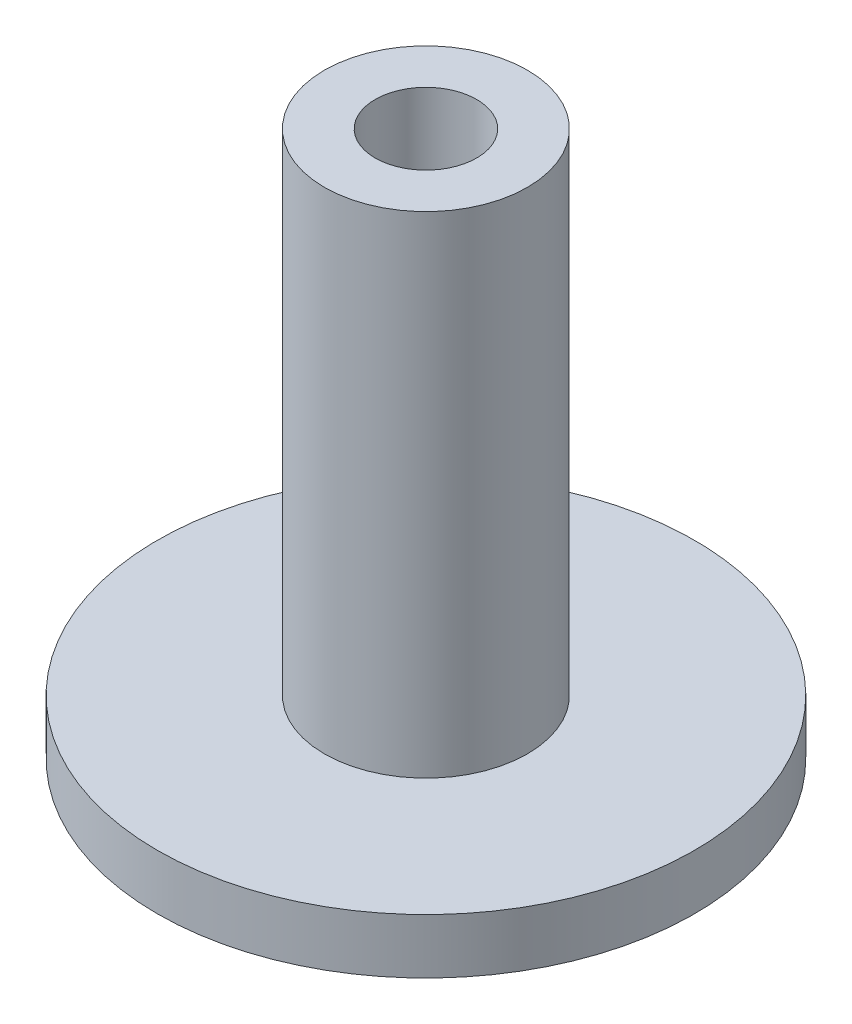
SolidWorks part; units mm, degrees
ref_plane "Front Plane" through (0, 0, 0) normal (0, 0, 1) x (1, 0, 0)
ref_plane "Top Plane" through (0, 0, 0) normal (0, 1, 0) x (1, 0, 0)
ref_plane "Right Plane" through (0, 0, 0) normal (1, 0, 0) x (0, 0, -1)
sketch "Sketch1" plane through (0, 0, 0) normal (0, 1, 0) x (1, 0, 0)
  circle A0 centre (0, 0) radius 6.35
  dimension "D1" = 12.7
extrude "Boss-Extrude1" add sketch "Sketch1" along normal blind 1.3
sketch "Sketch2" plane through (0, 1.3, 0) normal (0, 1, 0) x (1, 0, 0)
  circle A0 centre (0, 0) radius 2.4
  dimension "D1" = 4.8
extrude "Boss-Extrude2" add sketch "Sketch2" along normal blind 11.6
sketch "Sketch3" plane through (0, 12.9, 0) normal (0, 1, 0) x (1, 0, 0)
  circle A0 centre (0, 0) radius 1.2
  circle A1 centre (0, 0) radius 2.4 construction
  dimension "D1" = 1.2
extrude "Cut-Extrude1" cut sketch "Sketch3" against normal through all
